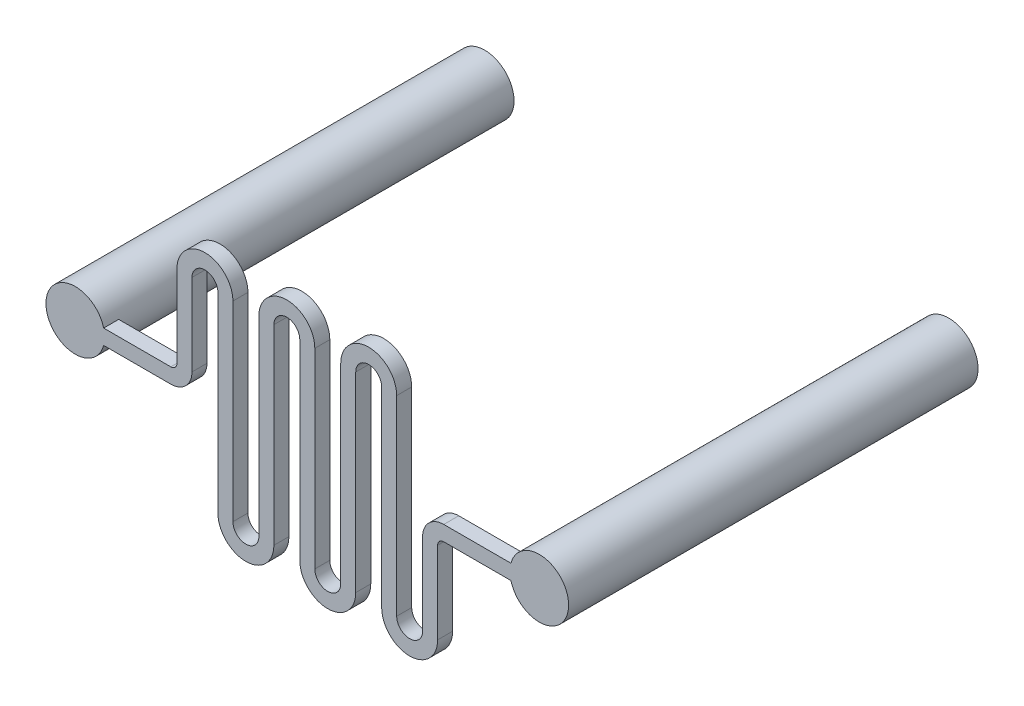
SolidWorks part; units mm, degrees
ref_plane "Front Plane" through (0, 0, 0) normal (0, 0, 1) x (1, 0, 0)
ref_plane "Top Plane" through (0, 0, 0) normal (0, 1, 0) x (1, 0, 0)
ref_plane "Right Plane" through (0, 0, 0) normal (1, 0, 0) x (0, 0, -1)
sketch "Sketch2" plane through (0, 0, 0) normal (0, 0, 1) x (1, 0, 0)
  line L3 (-20.5, -0.55) -> (-13.5, -0.55)
  line L6 (-11.95, 1) -> (-11.95, 7)
  line L9 (-10.05, 7) -> (-10.05, 0)
  line L12 (-10.05, 0) -> (-10.05, -7)
  line L15 (-5.95, -7) -> (-5.95, 0)
  line L18 (-5.95, 0) -> (-5.95, 7)
  line L21 (-4.05, 7) -> (-4.05, 0)
  line L22 (-4.05, 0) -> (-4.05, -7)
  line L23 (0.05, -7) -> (0.05, 0)
  line L24 (0.05, 0) -> (0.05, 7)
  line L25 (1.95, 7) -> (1.95, 0)
  line L26 (1.95, 0) -> (1.95, -7)
  line L27 (6.05, -7) -> (6.05, -1)
  line L28 (6.5, -0.55) -> (13.5, -0.55)
  line L29 (-20.5, 0.55) -> (-13.5, 0.55)
  line L30 (-13.05, 1) -> (-13.05, 7)
  line L31 (-8.95, 7) -> (-8.95, 0)
  line L32 (-8.95, 0) -> (-8.95, -7)
  line L33 (-7.05, -7) -> (-7.05, 0)
  line L34 (-7.05, 0) -> (-7.05, 7)
  line L35 (-2.95, 7) -> (-2.95, 0)
  line L36 (-2.95, 0) -> (-2.95, -7)
  line L37 (-1.05, -7) -> (-1.05, 0)
  line L38 (-1.05, 0) -> (-1.05, 7)
  line L39 (3.05, 7) -> (3.05, 0)
  line L40 (3.05, 0) -> (3.05, -7)
  line L41 (4.95, -7) -> (4.95, -1)
  line L42 (6.5, 0.55) -> (13.5, 0.55)
  arc A0 (13.5, -0.55) -> (13.5, 0.55) centre (13.5, 0) ccw
  arc A8 (-11.95, 1) -> (-13.5, -0.55) centre (-13.5, 1) cw
  arc A9 (-11.95, 7) -> (-10.05, 7) centre (-11, 7) cw
  arc A10 (-10.05, -7) -> (-5.95, -7) centre (-8, -7) ccw
  arc A11 (-5.95, 7) -> (-4.05, 7) centre (-5, 7) cw
  arc A12 (-4.05, -7) -> (0.05, -7) centre (-2, -7) ccw
  arc A13 (0.05, 7) -> (1.95, 7) centre (1, 7) cw
  arc A14 (1.95, -7) -> (6.05, -7) centre (4, -7) ccw
  arc A15 (6.05, -1) -> (6.5, -0.55) centre (6.5, -1) cw
  arc A16 (-13.05, 1) -> (-13.5, 0.55) centre (-13.5, 1) cw
  arc A17 (-13.05, 7) -> (-8.95, 7) centre (-11, 7) cw
  arc A18 (-8.95, -7) -> (-7.05, -7) centre (-8, -7) ccw
  arc A19 (-7.05, 7) -> (-2.95, 7) centre (-5, 7) cw
  arc A20 (-2.95, -7) -> (-1.05, -7) centre (-2, -7) ccw
  arc A21 (-1.05, 7) -> (3.05, 7) centre (1, 7) cw
  arc A22 (3.05, -7) -> (4.95, -7) centre (4, -7) ccw
  arc A23 (4.95, -1) -> (6.5, 0.55) centre (6.5, -1) cw
  arc A24 (-20.5, 0.55) -> (-20.5, -0.55) centre (-20.5, 0) ccw
  point P4 (0, 0)
  point P32 (5.5, 0)
  point P35 (-12.5, 0)
  dimension "D1" = 8
extrude "Boss-Extrude1" add sketch "Sketch2" along normal blind 1.1
ref_plane "Plane1" through (0, 0, 0) normal (0, -1, 0) x (-1, 0, 0)
sketch "Sketch3" plane through (0, 0, 0) normal (0, -1, 0) x (-1, 0, 0)
  line L1 (20.5, 28.9) -> (22.65, 28.9)
  line L2 (20.5, -1.1) -> (20.5, 28.9)
  line L6 (22.65, 28.9) -> (22.65, -1.1)
  line L7 (22.65, -1.1) -> (20.5, -1.1)
  dimension "D1" = 30
  dimension "D2" = 2.15
ref_plane "Plane2" through (0, 0, 0) normal (0, -1, 0) x (-1, 0, 0)
sketch "Sketch4" plane through (0, 0, 0) normal (0, -1, 0) x (-1, 0, 0)
  line L0 (-13.5, -1.1) -> (-15.65, -1.1)
  line L1 (-15.65, -1.1) -> (-15.65, 28.9)
  line L2 (-15.65, 28.9) -> (-13.5, 28.9)
  line L3 (-13.5, 28.9) -> (-13.5, -1.1)
  dimension "D1" = 2.15
  dimension "D2" = 30
revolve "Revolve1" add sketch "Sketch3" angle 360 about L2
revolve "Revolve2" add sketch "Sketch4" angle 360 about L3
sketch "Sketch5" plane through (0, 0, -28.9) normal (0, 0, -1) x (-1, 0, 0)
  circle A0 centre (20.5, 0) radius 1.5
  circle A1 centre (-13.5, 0) radius 1.5
  dimension "D1" = 3
  dimension "D2" = 3
extrude "Cut-Extrude1" cut sketch "Sketch5" against normal blind 28
